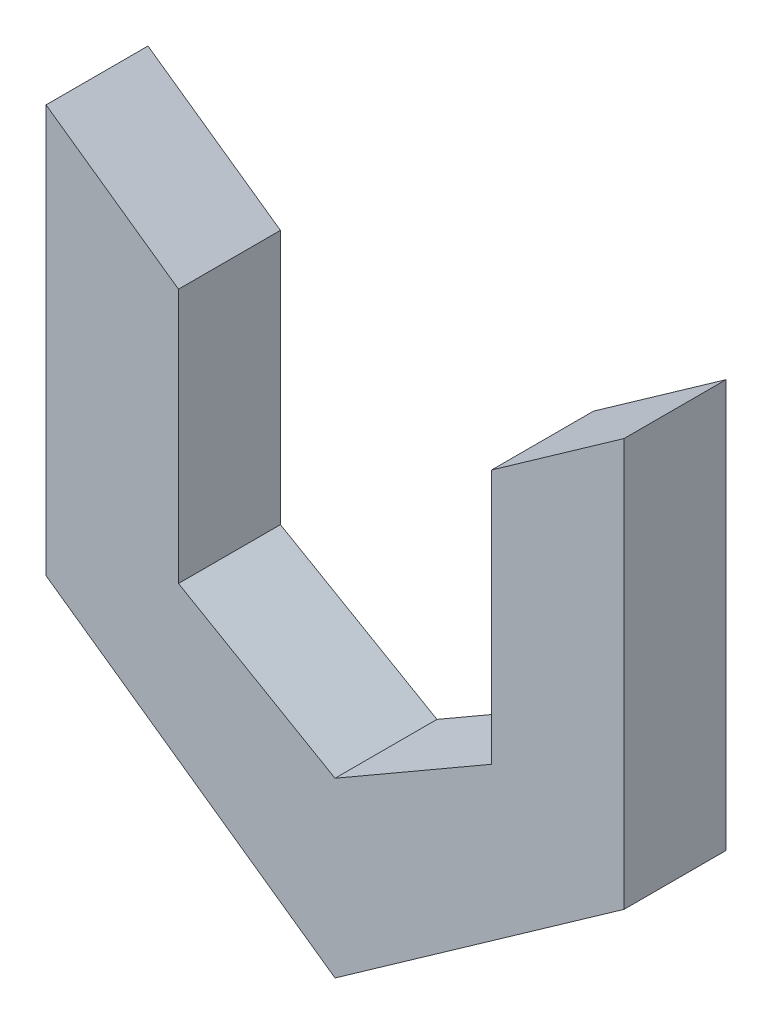
SolidWorks part; units mm, degrees
ref_plane "Front Plane" through (0, 0, 0) normal (0, 0, 1) x (1, 0, 0)
ref_plane "Top Plane" through (0, 0, 0) normal (0, 1, 0) x (1, 0, 0)
ref_plane "Right Plane" through (0, 0, 0) normal (1, 0, 0) x (0, 0, -1)
sketch "草图1" plane through (0, 0, 0) normal (0, 0, 1) x (1, 0, 0)
  line L0 (0, 0) -> (0, -40)
  line L1 (0, -40) -> (28.3461, -60)
  line L2 (28.3461, -60) -> (28.3461, -26.0623) construction
  line L3 (0, 0) -> (12.99, -9.1653)
  line L4 (12.99, -9.1653) -> (12.99, -34.1653)
  line L5 (12.99, -34.1653) -> (28.3461, -43.0311)
  line L6 (43.7022, -34.1653) -> (28.3461, -43.0311)
  line L7 (56.6922, -40) -> (28.3461, -60)
  line L8 (43.7022, -9.1653) -> (43.7022, -34.1653)
  line L9 (56.6922, 0) -> (43.7022, -9.1653)
  line L10 (56.6922, 0) -> (56.6922, -40)
  point P12 (56.6922, -20)
  point P13 (43.7022, -9.1653)
  dimension "D1" = 56.6922
  dimension "D2" = 25
  dimension "D3" = 12.99
  dimension "D4" = 12.99
  dimension "D5" = 40
  dimension "D6" = 60
  dimension "D7" = 120
extrude "凸台-拉伸1" add sketch "草图1" along normal blind 10
